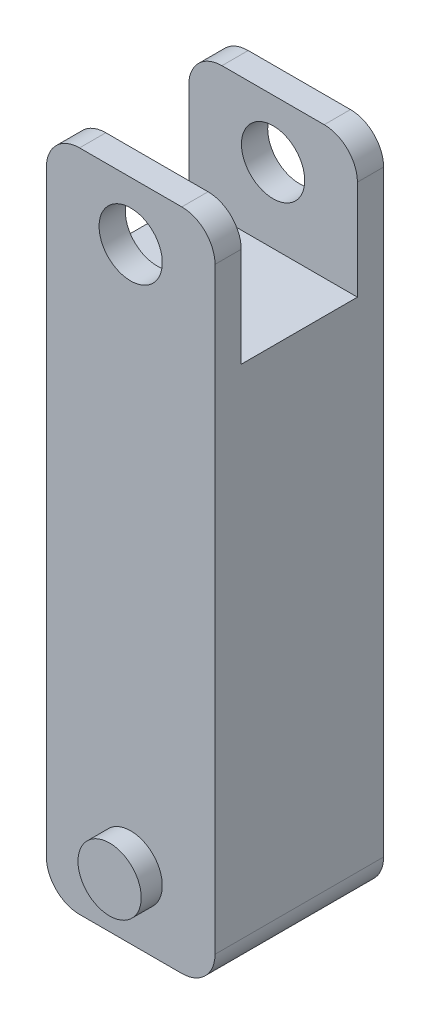
SolidWorks part; units mm, degrees
ref_plane "Alzado" through (0, 0, 0) normal (0, 0, 1) x (1, 0, 0)
ref_plane "Planta" through (0, 0, 0) normal (0, 1, 0) x (1, 0, 0)
ref_plane "Vista lateral" through (0, 0, 0) normal (1, 0, 0) x (0, 0, -1)
sketch "Croquis1" plane through (0, 0, 0) normal (0, 1, 0) x (1, 0, 0)
  line L1 (-50.8, -50.8) -> (50.8, -50.8)
  line L2 (-50.8, -50.8) -> (-50.8, 50.8)
  line L3 (-50.8, 50.8) -> (50.8, 50.8)
  line L4 (50.8, -50.8) -> (50.8, 50.8)
  line L5 (-50.8, -50.8) -> (50.8, 50.8) construction
  line L6 (-50.8, 50.8) -> (50.8, -50.8) construction
  point P0 (0, 0)
  dimension "D1" = 101.6
  dimension "D2" = 101.6
extrude "Saliente-Extruir1" add sketch "Croquis1" along normal blind 400
sketch "Croquis2" plane through (0, 0, 50.8) normal (0, 0, 1) x (1, 0, 0)
  line L0 (0, 0) -> (0, 40) construction
  line L1 (-50.8, 0) -> (50.8, 0) construction
  circle A0 centre (0, 40) radius 19.05
  dimension "D2" = 38.1
  dimension "D1" = 40
extrude "Saliente-Extruir2" add sketch "Croquis2" along normal blind 12.7
sketch "Croquis3" plane through (0, 0, -50.8) normal (0, 0, -1) x (-1, 0, 0)
  circle A0 centre (0, 40) radius 19.05
extrude "Saliente-Extruir3" add sketch "Croquis3" along normal blind 12.7
fillet "Redondeo1" radius 20 2 edges at (-50.8, 0, 0) (50.8, 0, 0)
sketch "Croquis5" plane through (50.8, 0, 0) normal (1, 0, 0) x (0, 0, -1)
  line L0 (0, 400) -> (0, 320) construction
  line L1 (-50.8, 400) -> (50.8, 400) construction
  line L3 (-35, 320) -> (35, 320)
  line L4 (-35, 320) -> (-35, 400)
  line L5 (-35, 400) -> (35, 400)
  line L6 (35, 320) -> (35, 400)
  line L7 (-35, 320) -> (35, 400) construction
  line L8 (-35, 400) -> (35, 320) construction
  point P5 (0, 360)
  dimension "D1" = 80
  dimension "D2" = 70
extrude "Cortar-Extruir1" cut sketch "Croquis5" against normal up to surface (101.6 mm away) up to face at (-50.8, 210, 0)
sketch "Croquis6" plane through (0, 0, -50.8) normal (0, 0, -1) x (-1, 0, 0)
  line L0 (0, 400) -> (0, 365) construction
  line L1 (-50.8, 400) -> (50.8, 400) construction
  circle A0 centre (0, 365) radius 19.05
  dimension "D2" = 38.1
  dimension "D1" = 35
extrude "Cortar-Extruir2" cut sketch "Croquis6" against normal up to surface (101.6 mm away) up to face at (-19.05, 40, 50.8)
fillet "Redondeo2" radius 20 4 edges at (-50.8, 400, 42.9) (-50.8, 400, -42.9) (50.8, 400, 42.9) (50.8, 400, -42.9)
